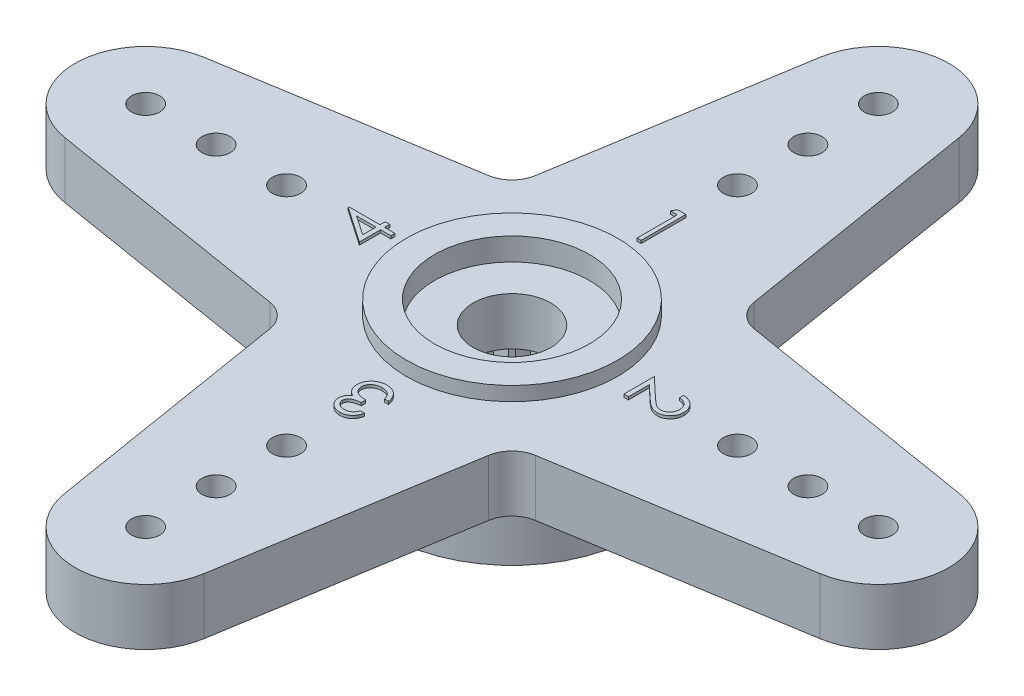
SolidWorks part; units mm, degrees
ref_plane "Front Plane" through (0, 0, 0) normal (0, 0, 1) x (1, 0, 0)
ref_plane "Top Plane" through (0, 0, 0) normal (0, 1, 0) x (1, 0, 0)
ref_plane "Right Plane" through (0, 0, 0) normal (1, 0, 0) x (0, 0, -1)
sketch "Sketch1" plane through (0, 0, 0) normal (0, 1, 0) x (1, 0, 0)
  line L0 (0, 15.5) -> (0, -15.5) construction
  line L1 (-15.5, 0) -> (15.5, 0) construction
  line L2 (-2.4674, 13.4022) -> (-4, 4) construction
  line L3 (4, -4) -> (-4, -4) construction
  line L4 (4, -4) -> (4, 4) construction
  line L5 (4, 4) -> (-4, 4) construction
  line L6 (-4, -4) -> (-4, 4) construction
  line L7 (4, -4) -> (-4, 4) construction
  line L8 (4, 4) -> (-4, -4) construction
  line L9 (-4, 4) -> (-2.4674, 13.4022)
  line L10 (4, 4) -> (2.4674, 13.4022)
  line L11 (4, 4) -> (13.4022, 2.4674)
  line L12 (4, -4) -> (13.4022, -2.4674)
  line L13 (4, -4) -> (2.4674, -13.4022)
  line L14 (-4, -4) -> (-2.4674, -13.4022)
  line L15 (-4, -4) -> (-13.4022, -2.4674)
  line L16 (-4, 4) -> (-13.4022, 2.4674)
  circle A0 centre (0, 0) radius 15.5 construction
  arc A1 (13.4022, -2.4674) -> (13.4022, 2.4674) centre (13, 0) ccw
  arc A2 (2.4674, 13.4022) -> (-2.4674, 13.4022) centre (0, 13) ccw
  circle A3 centre (13, 0) radius 0.5
  circle A4 centre (10.5, 0) radius 0.5
  circle A5 centre (8, 0) radius 0.5
  circle A6 centre (0, 0) radius 13 construction
  circle A7 centre (0, 0) radius 10.5 construction
  circle A8 centre (0, 0) radius 8 construction
  circle A9 centre (0, 13) radius 0.5
  circle A10 centre (0, 10.5) radius 0.5
  circle A11 centre (0, 8) radius 0.5
  arc A12 (-2.4674, -13.4022) -> (2.4674, -13.4022) centre (0, -13) ccw
  circle A13 centre (0, -13) radius 0.5
  circle A14 centre (0, -10.5) radius 0.5
  circle A15 centre (0, -8) radius 0.5
  arc A16 (-13.4022, 2.4674) -> (-13.4022, -2.4674) centre (-13, 0) ccw
  circle A17 centre (-13, 0) radius 0.5
  circle A18 centre (-10.5, 0) radius 0.5
  circle A19 centre (-8, 0) radius 0.5
  circle A21 centre (0, 0) radius 1.375
  point P59 (0, 0)
  point P63 (0, 0)
  dimension "D1" = 31
  dimension "D2" = 4
  dimension "D3" = 5
  dimension "D5" = 8
  dimension "D6" = 8
  dimension "D7" = 16
  dimension "D9" = 26
  dimension "D11" = 1
  dimension "D12" = 1
  dimension "D8" = 21
  dimension "D10" = 1
  dimension "D14" = 2.75
extrude "Boss-Extrude1" add sketch "Sketch1" along normal blind 2
sketch "Sketch2" plane through (0, 2, 0) normal (0, 1, 0) x (1, 0, 0)
  circle A0 centre (0, 0) radius 3.75
  circle A1 centre (0, 0) radius 2.75
  dimension "D1" = 7.5
  dimension "D2" = 1
extrude "Boss-Extrude2" add sketch "Sketch2" along normal blind 0.5
sketch "Sketch3" plane through (0, 2.5, 0) normal (0, 1, 0) x (1, 0, 0)
  circle A2 centre (0, 0) radius 1.375
  circle A3 centre (0, 0) radius 2.75
  circle A5 centre (0, 0) radius 2.75
  circle A6 centre (0, 0) radius 2.75
  circle M6 centre (0, 0) radius 2.75
  dimension "D1" = 0
extrude "Cut-Extrude1" cut sketch "Sketch3" against normal blind 0.8 contours A2 M6
sketch "Sketch4" plane through (0, 0, 0) normal (0, -1, 0) x (1, 0, 0)
  circle A0 centre (0, 0) radius 4.5
  circle A1 centre (0, 0) radius 2.5
  dimension "D1" = 9
  dimension "D2" = 2
extrude "Boss-Extrude3" add sketch "Sketch4" along normal blind 2.5
sketch "Sketch5" plane through (0, -2.5, 0) normal (0, -1, 0) x (1, 0, 0)
  line L0 (0, 0) -> (0, 0.6245) construction
  line L1 (0, 3) -> (-0.299, 2.4821)
  line L2 (0, 3) -> (0.299, 2.4821)
  line L3 (0.9271, 2.8532) -> (0.4826, 2.453)
  line L4 (0.9271, 2.8532) -> (1.0514, 2.2682)
  line L5 (1.7634, 2.4271) -> (1.217, 2.1838)
  line L6 (1.7634, 2.4271) -> (1.7008, 1.8323)
  line L7 (2.4271, 1.7634) -> (1.8323, 1.7008)
  line L8 (2.4271, 1.7634) -> (2.1838, 1.217)
  line L9 (2.8532, 0.9271) -> (2.2682, 1.0514)
  line L10 (2.8532, 0.9271) -> (2.453, 0.4826)
  line L11 (3, 0) -> (2.4821, 0.299)
  line L12 (3, 0) -> (2.4821, -0.299)
  line L13 (2.8532, -0.9271) -> (2.453, -0.4826)
  line L14 (2.8532, -0.9271) -> (2.2682, -1.0514)
  line L15 (2.4271, -1.7634) -> (2.1838, -1.217)
  line L16 (2.4271, -1.7634) -> (1.8323, -1.7008)
  line L17 (1.7634, -2.4271) -> (1.7008, -1.8323)
  line L18 (1.7634, -2.4271) -> (1.217, -2.1838)
  line L19 (0.9271, -2.8532) -> (1.0514, -2.2682)
  line L20 (0.9271, -2.8532) -> (0.4826, -2.453)
  line L21 (0, -3) -> (0.299, -2.4821)
  line L22 (0, -3) -> (-0.299, -2.4821)
  line L23 (-0.9271, -2.8532) -> (-0.4826, -2.453)
  line L24 (-0.9271, -2.8532) -> (-1.0514, -2.2682)
  line L25 (-1.7634, -2.4271) -> (-1.217, -2.1838)
  line L26 (-1.7634, -2.4271) -> (-1.7008, -1.8323)
  line L27 (-2.4271, -1.7634) -> (-1.8323, -1.7008)
  line L28 (-2.4271, -1.7634) -> (-2.1838, -1.217)
  line L29 (-2.8532, -0.9271) -> (-2.2682, -1.0514)
  line L30 (-2.8532, -0.9271) -> (-2.453, -0.4826)
  line L31 (-3, 0) -> (-2.4821, -0.299)
  line L32 (-3, 0) -> (-2.4821, 0.299)
  line L33 (-2.8532, 0.9271) -> (-2.453, 0.4826)
  line L34 (-2.8532, 0.9271) -> (-2.2682, 1.0514)
  line L35 (-2.4271, 1.7634) -> (-2.1838, 1.217)
  line L36 (-2.4271, 1.7634) -> (-1.8323, 1.7008)
  line L37 (-1.7634, 2.4271) -> (-1.7008, 1.8323)
  line L38 (-1.7634, 2.4271) -> (-1.217, 2.1838)
  line L39 (-0.9271, 2.8532) -> (-1.0514, 2.2682)
  line L40 (-0.9271, 2.8532) -> (-0.4826, 2.453)
  circle A0 centre (0, 0) radius 2.5 construction
  arc A1 (-2.1838, 1.217) -> (-2.2682, 1.0514) centre (0, 0) ccw
  arc A2 (-1.7008, 1.8323) -> (-1.8323, 1.7008) centre (0, 0) ccw
  arc A3 (-1.0514, 2.2682) -> (-1.217, 2.1838) centre (0, 0) ccw
  arc A4 (-0.299, 2.4821) -> (-0.4826, 2.453) centre (0, 0) ccw
  arc A5 (0.4826, 2.453) -> (0.299, 2.4821) centre (0, 0) ccw
  arc A6 (1.217, 2.1838) -> (1.0514, 2.2682) centre (0, 0) ccw
  arc A7 (1.8323, 1.7008) -> (1.7008, 1.8323) centre (0, 0) ccw
  arc A8 (2.2682, 1.0514) -> (2.1838, 1.217) centre (0, 0) ccw
  arc A9 (2.4821, 0.299) -> (2.453, 0.4826) centre (0, 0) ccw
  arc A10 (2.453, -0.4826) -> (2.4821, -0.299) centre (0, 0) ccw
  arc A11 (2.1838, -1.217) -> (2.2682, -1.0514) centre (0, 0) ccw
  arc A12 (1.7008, -1.8323) -> (1.8323, -1.7008) centre (0, 0) ccw
  arc A13 (1.0514, -2.2682) -> (1.217, -2.1838) centre (0, 0) ccw
  arc A14 (0.299, -2.4821) -> (0.4826, -2.453) centre (0, 0) ccw
  arc A15 (-0.4826, -2.453) -> (0, -2.5) centre (0, 0) ccw
  arc A16 (-1.217, -2.1838) -> (-1.0514, -2.2682) centre (0, 0) ccw
  arc A17 (-1.8323, -1.7008) -> (-1.7008, -1.8323) centre (0, 0) ccw
  arc A18 (-2.2682, -1.0514) -> (-2.1838, -1.217) centre (0, 0) ccw
  arc A19 (-2.4821, -0.299) -> (-2.453, -0.4826) centre (0, 0) ccw
  arc A20 (-2.453, 0.4826) -> (-2.4821, 0.299) centre (0, 0) ccw
  point P68 (0, 0)
  circle M5 centre (0, 0) radius 2.5
  dimension "D1" = 30
  dimension "D2" = 3
  dimension "D3" = 20
extrude "Cut-Extrude3" cut sketch "Sketch5" against normal up to surface (2.5 mm away) contours L36 L35 M5 | L34 L33 M5 | L32 L31 M5 | L30 L29 M5 | L28 L27 M5 | L26 L25 M5 | L24 L23 M5 | L0 L21 M5 | L22 L0 M5 | L20 L19 M5 | L18 L17 M5 | L16 L15 M5 | L14 L13 M5 | L12 L11 M5 | L10 L9 M5 | L8 L7 M5 | L6 L5 M5 | L4 L3 M5 | L0 L2 M5 | L0 L1 M5 | L40 L39 M5 | L38 L37 M5
sketch "Sketch6" plane through (0, 2, 0) normal (0, 1, 0) x (1, 0, 0)
  line L1 (4.5, -4.5) -> (-4.5, -4.5) construction
  line L2 (4.5, -4.5) -> (4.5, 4.5) construction
  line L3 (4.5, 4.5) -> (-4.5, 4.5) construction
  line L4 (-4.5, -4.5) -> (-4.5, 4.5) construction
  line L5 (4.5, -4.5) -> (-4.5, 4.5) construction
  line L6 (4.5, 4.5) -> (-4.5, -4.5) construction
  circle A0 centre (0, 0) radius 4.5 construction
  text T0 "1" font "Century Gothic" height in points 6
  text T1 "2" font "Century Gothic" height in points 6
  text T2 "3" font "Century Gothic" height in points 6
  text T3 "4" font "Century Gothic" height in points 6
  dimension "D1" = 9
  dimension "D2" = 9
  dimension "D3" = 9
extrude "Boss-Extrude4" add sketch "Sketch6" along normal blind 0.1
fillet "Fillet1" radius 1 4 edges at (-4, 1, 4) (4, 1, 4) (4, 1, -4) (-4, 1, -4)
